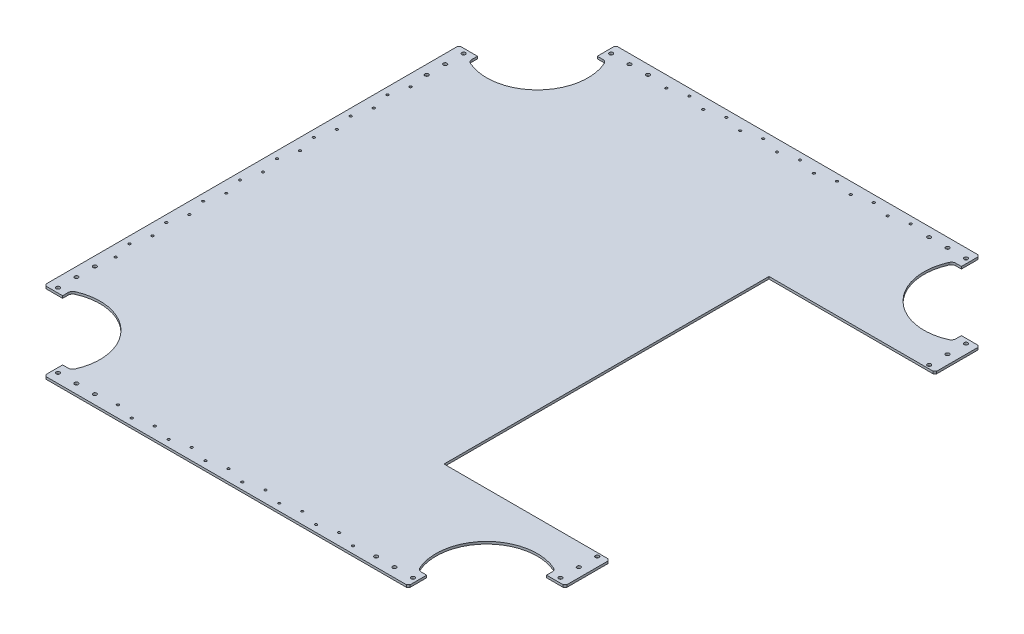
SolidWorks part; units mm, degrees
material "6061-T6 (SS)"
ref_plane "Front Plane" through (0, 0, 0) normal (0, 0, 1) x (1, 0, 0)
ref_plane "Top Plane" through (0, 0, 0) normal (0, 1, 0) x (1, 0, 0)
ref_plane "Right Plane" through (0, 0, 0) normal (1, 0, 0) x (0, 0, -1)
sketch "Sketch1" plane through (0, 0, 0) normal (0, 1, 0) x (1, 0, 0)
  line L1 (-358.775, -393.7) -> (358.775, -393.7)
  line L2 (-358.775, -393.7) -> (-358.775, 393.7)
  line L3 (-358.775, 393.7) -> (358.775, 393.7)
  line L4 (358.775, -393.7) -> (358.775, 393.7)
  line L5 (-358.775, -393.7) -> (358.775, 393.7) construction
  line L6 (-358.775, 393.7) -> (358.775, -393.7) construction
  point P0 (0, 0)
  dimension "D1" = 717.55
  dimension "D2" = 787.4
extrude "Boss-Extrude1" add sketch "Sketch1" along normal blind 3.175
sketch "Sketch8" plane through (0, 3.175, 0) normal (0, 1, 0) x (1, 0, 0)
  line L0 (358.775, 393.7) -> (-358.775, 393.7) construction
  line L1 (358.775, -393.7) -> (358.775, 393.7) construction
  line L4 (358.775, 285.7557) -> (358.775, 393.7)
  line L5 (358.775, 393.7) -> (250.8307, 393.7)
  line L6 (-1.7463, 0) -> (1.7463, 0) construction
  line L11 (333.375, -285.7557) -> (333.375, -274.1479)
  line L20 (250.8307, 393.7) -> (250.8307, 368.3)
  line L21 (250.8307, 368.3) -> (239.2229, 368.3)
  line L22 (358.775, 285.7557) -> (333.375, 285.7557)
  line L23 (333.375, 285.7557) -> (333.375, 274.1479)
  line L24 (358.775, -285.7557) -> (333.375, -285.7557)
  line L25 (250.8307, -368.3) -> (239.2229, -368.3)
  line L26 (250.8307, -393.7) -> (250.8307, -368.3)
  line L27 (358.775, -393.7) -> (250.8307, -393.7)
  line L28 (358.775, -285.7557) -> (358.775, -393.7)
  line L29 (0, -1.7463) -> (0, 1.7463) construction
  line L30 (-358.775, -285.7557) -> (-358.775, -393.7)
  line L31 (-358.775, -393.7) -> (-250.8307, -393.7)
  line L32 (-250.8307, -393.7) -> (-250.8307, -368.3)
  line L33 (-250.8307, -368.3) -> (-239.2229, -368.3)
  line L34 (-358.775, -285.7557) -> (-333.375, -285.7557)
  line L35 (-333.375, 285.7557) -> (-333.375, 274.1479)
  line L36 (-358.775, 285.7557) -> (-333.375, 285.7557)
  line L37 (-250.8307, 368.3) -> (-239.2229, 368.3)
  line L38 (-250.8307, 393.7) -> (-250.8307, 368.3)
  line L39 (-333.375, -285.7557) -> (-333.375, -274.1479)
  line L40 (-358.775, 393.7) -> (-250.8307, 393.7)
  line L41 (-358.775, 285.7557) -> (-358.775, 393.7)
  arc A0 (239.2229, 368.3) -> (333.375, 274.1479) centre (301.244, 336.169) ccw
  arc A1 (239.2229, -368.3) -> (333.375, -274.1479) centre (301.244, -336.169) cw
  arc A2 (-239.2229, -368.3) -> (-333.375, -274.1479) centre (-301.244, -336.169) ccw
  arc A3 (-239.2229, 368.3) -> (-333.375, 274.1479) centre (-301.244, 336.169) cw
  dimension "D1" = 139.7
  dimension "D2" = 57.531
  dimension "D3" = 57.531
  dimension "D6" = 11.6078
  dimension "D5" = 25.4
extrude "Swerve Cutout" cut sketch "Sketch8" against normal through all
sketch "Sketch2" plane through (0, 3.175, 0) normal (0, 1, 0) x (1, 0, 0)
  line L23 (358.775, -223.8375) -> (130.175, -223.8375)
  line L24 (358.775, -285.7557) -> (358.775, 285.7557) construction
  line L25 (130.175, -223.8375) -> (130.175, 223.8375)
  line L26 (130.175, 223.8375) -> (358.775, 223.8375)
  line L27 (358.775, 223.8375) -> (358.775, -223.8375)
  point P1 (358.775, 0)
  point P7 (358.775, 0)
  dimension "D1" = 447.675
  dimension "D2" = 228.6
extrude "Intake Cutout" cut sketch "Sketch2" against normal blind 3.175
hole_wizard "#8 (0.199) Diameter Hole1" positions "Sketch10" profile "Sketch11" hole size "#8" standard "ANSI Inch" end condition through all
sketch "Sketch10" plane through (0, 3.175, 0) normal (0, 1, 0) x (1, 0, 0)
  line L0 (250.8307, 381) -> (193.6807, 381) construction
  line L1 (250.8307, 393.7) -> (250.8307, 368.3) construction
  line L2 (346.075, 285.7557) -> (346.075, 223.8375) construction
  line L3 (358.775, 285.7557) -> (333.375, 285.7557) construction
  line L4 (358.775, 223.8375) -> (130.175, 223.8375) construction
  line L5 (-1.7463, 0) -> (1.7463, 0) construction
  line L6 (346.075, -285.7557) -> (346.075, -223.8375) construction
  line L7 (250.8307, -381) -> (193.6807, -381) construction
  line L8 (0, -1.7463) -> (0, 1.7463) construction
  line L9 (-250.8307, -381) -> (-193.6807, -381) construction
  line L10 (-346.075, -285.7557) -> (-346.075, -223.8375) construction
  line L11 (-346.075, 285.7557) -> (-346.075, 223.8375) construction
  line L12 (-250.8307, 381) -> (-193.6807, 381) construction
  point P0 (244.4807, 381)
  point P2 (219.0807, 381)
  point P4 (193.6807, 381)
  point P18 (346.075, 279.4057)
  point P20 (346.075, 254.0057)
  point P22 (346.075, 228.6057)
  point P31 (346.075, -228.6057)
  point P32 (346.075, -254.0057)
  point P33 (346.075, -279.4057)
  point P34 (193.6807, -381)
  point P35 (219.0807, -381)
  point P36 (244.4807, -381)
  point P47 (-244.4807, -381)
  point P48 (-219.0807, -381)
  point P49 (-193.6807, -381)
  point P50 (-346.075, -279.4057)
  point P51 (-346.075, -254.0057)
  point P52 (-346.075, -228.6057)
  point P53 (-346.075, 228.6057)
  point P54 (-346.075, 254.0057)
  point P55 (-346.075, 279.4057)
  point P56 (-193.6807, 381)
  point P57 (-219.0807, 381)
  point P58 (-244.4807, 381)
  dimension "D1" = 6.35
  dimension "D2" = 6.35
  dimension "D3" = 31.75
  dimension "D4" = 57.15
  dimension "D5" = 31.75
  dimension "D6" = 57.15
sketch "Sketch11" plane through (244.4807, 3.175, -381) normal (1, 0, 0) x (0, 0, 1)
  line L0 (0, 0) -> (0, 3.175)
  line L1 (0, 3.175) -> (2.5273, 3.175)
  line L2 (2.5273, 3.175) -> (2.5273, 0)
  line L5 (2.5273, 0) -> (0, 0)
  line L11 (0, -6.35) -> (0, 107.95) construction
  dimension "Thru Hole Dia." = 5.0546
  dimension "Thru Hole Depth" = 3.175
sketch "Sketch3" plane through (0, 3.175, 0) normal (0, 1, 0) x (1, 0, 0)
  line L0 (-76.2, 368.3) -> (-76.2, 203.2)
  line L1 (250.8307, 393.7) -> (-250.8307, 393.7) construction
  line L2 (-76.2, 203.2) -> (76.2, 203.2)
  line L3 (76.2, 203.2) -> (76.2, 368.3)
  line L4 (76.2, 368.3) -> (-76.2, 368.3)
  line L6 (-76.2, -368.3) -> (76.2, -368.3)
  line L7 (76.2, -368.3) -> (76.2, -203.2)
  line L8 (76.2, -203.2) -> (-76.2, -203.2)
  line L9 (-76.2, -203.2) -> (-76.2, -368.3)
  line L10 (250.8307, 393.7) -> (-250.8307, 393.7) construction
  line L12 (0, 393.7) -> (0, 368.3) construction
  line L13 (-250.8307, -393.7) -> (250.8307, -393.7) construction
  dimension "D1" = 165.1
  dimension "D2" = 152.4
  dimension "D3" = 25.4
  dimension "D4" = 25.4
extrude "Climber Cutout" [suppressed] cut sketch "Sketch3" against normal blind 3.175
hole_wizard "#30 (0.1285) Diameter Hole1" positions "Sketch5" profile "Sketch6" hole size "#30" standard "ANSI Inch"
sketch "Sketch5" plane through (0, 3.175, 0) normal (0, 1, 0) x (1, 0, 0)
  line L1 (250.8307, 393.7) -> (-250.8307, 393.7) construction
  line L2 (-165.1, 377.825) -> (-250.8307, 377.825) construction
  line L3 (-250.8307, 393.7) -> (-250.8307, 368.3) construction
  line L5 (165.1, 384.175) -> (250.8307, 384.175) construction
  line L6 (250.8307, 393.7) -> (250.8307, 368.3) construction
  line L8 (-1.7463, 0) -> (1.7463, 0) construction
  line L9 (165.1, -384.175) -> (250.8307, -384.175) construction
  line L10 (-165.1, -377.825) -> (-250.8307, -377.825) construction
  line L11 (-358.775, 285.7557) -> (-358.775, -285.7557) construction
  line L12 (-342.9, -203.2) -> (-342.9, -285.7557) construction
  line L13 (-358.775, -285.7557) -> (-333.375, -285.7557) construction
  line L15 (-342.9, 203.2) -> (-342.9, 285.7557) construction
  line L16 (-358.775, 285.7557) -> (-333.375, 285.7557) construction
  point P4 (-139.7, 384.175)
  point P6 (-114.3, 377.825)
  point P13 (-88.9, 384.175)
  point P14 (-88.9, 384.175)
  point P16 (-88.9, 384.175)
  point P43 (-63.5, 377.825)
  point P44 (-38.1, 384.175)
  point P46 (-12.7, 377.825)
  point P47 (12.7, 384.175)
  point P49 (38.1, 377.825)
  point P50 (63.5, 384.175)
  point P52 (88.9, 377.825)
  point P53 (114.3, 384.175)
  point P55 (139.7, 377.825)
  point P56 (165.1, 384.175)
  point P64 (-88.9, 384.175)
  point P66 (-38.1, 384.175)
  point P68 (12.7, 384.175)
  point P70 (63.5, 384.175)
  point P72 (114.3, 384.175)
  point P74 (165.1, 384.175)
  point P76 (215.9, 384.175)
  point P330 (361.95, -170.9053)
  point P382 (190.5, 377.825)
  point P446 (-165.1, 377.825)
  point P557 (-358.775, 101.6)
  point P559 (-358.775, 50.8)
  point P561 (-358.775, 0)
  point P563 (-358.775, -50.8)
  point P565 (-358.775, -101.6)
  point P708 (-165.1, -377.825)
  point P709 (165.1, -384.175)
  point P710 (139.7, -377.825)
  point P711 (114.3, -384.175)
  point P712 (88.9, -377.825)
  point P713 (63.5, -384.175)
  point P714 (38.1, -377.825)
  point P715 (12.7, -384.175)
  point P716 (-12.7, -377.825)
  point P717 (-38.1, -384.175)
  point P718 (-63.5, -377.825)
  point P719 (-88.9, -384.175)
  point P720 (-114.3, -377.825)
  point P721 (-139.7, -384.175)
  point P724 (-342.9, -203.2)
  point P726 (-349.25, -177.8)
  point P728 (-342.9, -152.4)
  point P754 (-349.25, -127)
  point P755 (-342.9, -101.6)
  point P758 (-349.25, -76.2)
  point P759 (-342.9, -50.8)
  point P762 (-349.25, -25.4)
  point P763 (-342.9, 0)
  point P766 (-349.25, 25.4)
  point P767 (-342.9, 50.8)
  point P770 (-349.25, 76.2)
  point P771 (-342.9, 101.6)
  point P774 (-349.25, 127)
  point P775 (-342.9, 152.4)
  point P778 (-349.25, 177.8)
  point P779 (-342.9, 203.2)
  point P795 (-349.25, -165.1)
  point P797 (-342.9, -152.4)
  point P799 (-349.25, -114.3)
  point P801 (-342.9, -101.6)
  point P803 (-349.25, -63.5)
  point P805 (-342.9, -50.8)
  point P807 (-349.25, -12.7)
  point P809 (-342.9, 0)
  point P811 (-349.25, 38.1)
  point P813 (-342.9, 50.8)
  point P815 (-349.25, 88.9)
  point P817 (-342.9, 101.6)
  point P819 (-349.25, 139.7)
  point P821 (-342.9, 152.4)
  dimension "D1" = 25.4
  dimension "D2" = 25.4
  dimension "D3" = 9.525
  dimension "D4" = 15.875
  dimension "D5" = 9.525
  dimension "D7" = 50.8
  dimension "D9" = 25.4
  dimension "D11" = 15.875
  dimension "D12" = 8
  dimension "D13" = 25.4
  dimension "D18" = 25.4
  dimension "D8" = 25.4
  dimension "D6" = 7
sketch "Sketch6" plane through (-139.7, 3.175, -384.175) normal (1, 0, 0) x (0, 0, 1)
  line L0 (0, 0) -> (0, 3.175)
  line L1 (0, 3.175) -> (1.6319, 3.175)
  line L2 (1.6319, 3.175) -> (1.6319, 0)
  line L5 (1.6319, 0) -> (0, 0)
  line L11 (0, -6.35) -> (0, 107.95) construction
  dimension "Thru Hole Dia." = 3.2639
  dimension "Thru Hole Depth" = 3.175
fillet "Fillet1" radius 6.35 8 edges at (333.375, 1.5875, 274.1479) (239.2229, 1.5875, 368.3) (-333.375, 1.5875, 274.1479) (-239.2229, 1.5875, 368.3) (333.375, 1.5875, -274.1479) (239.2229, 1.5875, -368.3) (-239.2229, 1.5875, -368.3) (-333.375, 1.5875, -274.1479)
chamfer "Chamfer1" distance 2.54 angle 45 10 edges at (358.775, 1.5875, -223.8375) (250.8307, 1.5875, -393.7) (358.775, 1.5875, -285.7557) (-250.8307, 1.5875, -393.7) (-358.775, 1.5875, -285.7557) (-358.775, 1.5875, 285.7557) (-250.8307, 1.5875, 393.7) (250.8307, 1.5875, 393.7) (358.775, 1.5875, 223.8375) (358.775, 1.5875, 285.7557)
fillet "Fillet2" [suppressed] radius 6.35
